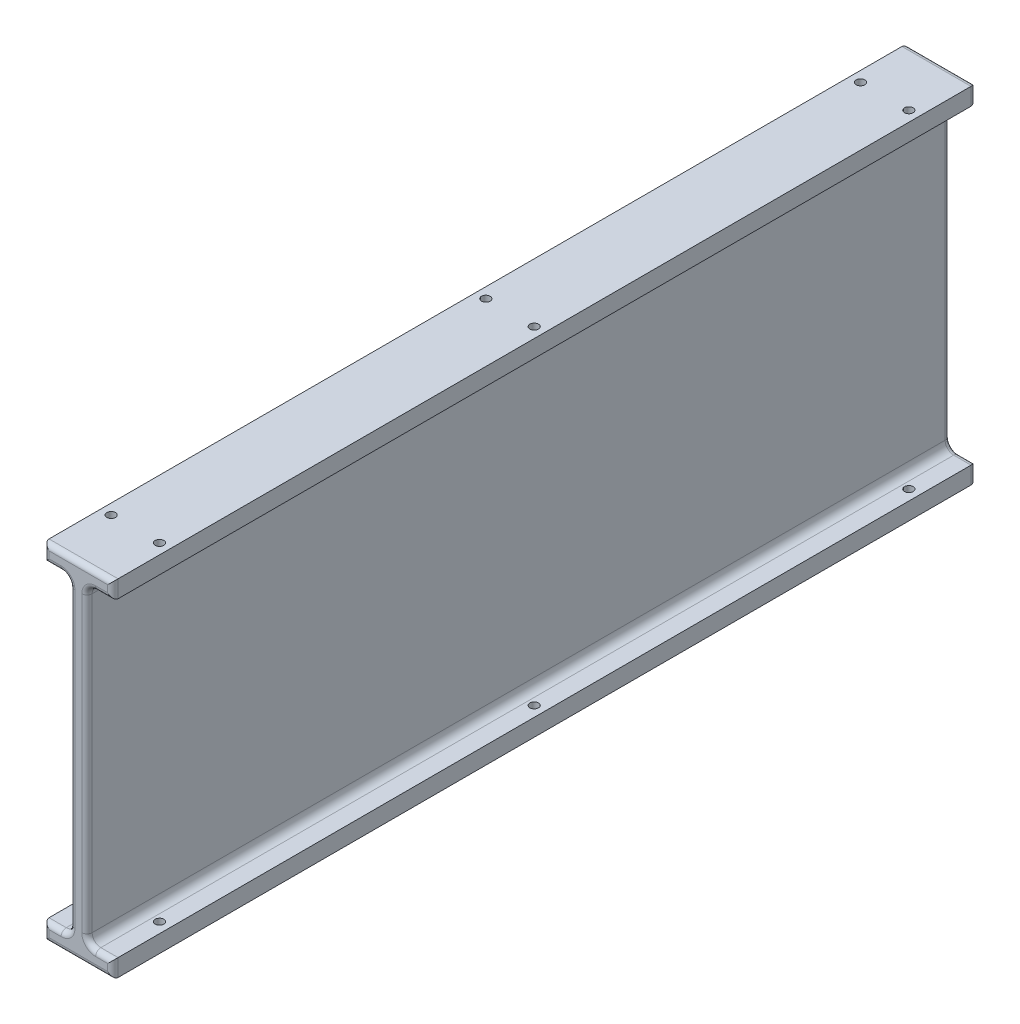
SolidWorks part; units mm, degrees
ref_plane "Front Plane" through (0, 0, 0) normal (0, 0, 1) x (1, 0, 0)
ref_plane "Top Plane" through (0, 0, 0) normal (0, 1, 0) x (1, 0, 0)
ref_plane "Right Plane" through (0, 0, 0) normal (1, 0, 0) x (0, 0, -1)
sketch "Sketch2" plane through (0, 0, 0) normal (0, 0, 1) x (1, 0, 0)
  line L0 (-5, 100) -> (5, 100)
  line L2 (-5, 96.25) -> (-5, 93.75)
  line L3 (-5, -100) -> (5, -100)
  line L4 (5, 85) -> (5, -85)
  line L5 (-4.8101, 96.2025) -> (-4.6914, 93.8272) construction
  line L7 (-20, -90) -> (-10, -90)
  line L8 (-20, -90) -> (-20, -100)
  line L9 (-20, -100) -> (20, -100)
  line L10 (20, -90) -> (20, -100)
  line L17 (4.6914, 93.8272) -> (5, 93.75) construction
  line L18 (-20, 90) -> (-10, 90)
  line L19 (-20, 90) -> (-20, 100)
  line L20 (-20, 100) -> (20, 100)
  line L21 (20, 90) -> (20, 100)
  line L22 (-5, 93.75) -> (-4.6914, 93.8272) construction
  line L23 (-5, 96.25) -> (-4.8101, 96.2025) construction
  line L24 (10, 90) -> (20, 90)
  line L25 (-4.5, 90) -> (4.5, -90) construction
  line L26 (-5, 85) -> (-5, -85)
  line L29 (-4.5, -90) -> (4.5, 90) construction
  line L31 (4.8101, -96.2025) -> (5, -96.25) construction
  line L32 (10, -90) -> (20, -90)
  arc A0 (5, -85) -> (10, -90) centre (10, -85) ccw
  arc A1 (-5, -85) -> (-10, -90) centre (-10, -85) cw
  arc A2 (5, 85) -> (10, 90) centre (10, 85) cw
  arc A3 (-5, 85) -> (-10, 90) centre (-10, 85) ccw
  point P0 (0, 0)
  point P6 (0, -95)
  point P11 (0, -100)
  point P12 (0, 95)
  point P18 (0, 100)
  point P31 (5, -90)
  dimension "D9" = 5
  dimension "D1" = 200
  dimension "D2" = 10
  dimension "D3" = 10
  dimension "D4" = 40
  dimension "D5" = 0
  dimension "D6" = 40
  dimension "D7" = 10
  dimension "D8" = 0
extrude "Boss-Extrude1" add sketch "Sketch2" along normal mid plane 500
fillet "Fillet1" radius 3 32 edges at (-5, 0, -250) (-6.4645, -88.5355, -250) (-15, -90, -250) (-20, -95, -250) (0, -100, -250) (20, -95, -250) (15, -90, -250) (6.4645, -88.5355, -250) (5, 0, -250) (6.4645, 88.5355, -250) (15, 90, -250) (20, 95, -250) (0, 100, -250) (-20, 95, -250) (-15, 90, -250) (-6.4645, 88.5355, -250) (-15, 90, 250) (-20, 95, 250) (0, 100, 250) (20, 95, 250) (15, 90, 250) (6.4645, 88.5355, 250) (5, 0, 250) (6.4645, -88.5355, 250) (15, -90, 250) (20, -95, 250) (0, -100, 250) (-20, -95, 250) (-15, -90, 250) (-6.4645, -88.5355, 250) (-5, 0, 250) (-6.4645, 88.5355, 250)
hole_wizard "Ø5.0mm Dowel Hole1" positions "Sketch6" profile "Sketch7" hole size "Ø5.0" standard "ANSI Metric" end condition through all
sketch "Sketch6" plane through (0, 100, 0) normal (0, 1, 0) x (1, 0, 0)
  line L0 (20, -247) -> (20, 247) construction
  line L1 (-20, -247) -> (-20, 247) construction
  line L2 (20, 247) -> (-20, 247) construction
  line L3 (-20, -247) -> (20, -247) construction
  point P0 (14, 217)
  point P5 (-14, 217)
  point P7 (-14, -217)
  point P9 (14, -217)
  point P18 (-14, 0)
  point P20 (14, 0)
  dimension "D1" = 6
  dimension "D2" = 6
  dimension "D3" = 30
  dimension "D4" = 30
  dimension "D5" = 30
  dimension "D6" = 30
  dimension "D7" = 6
  dimension "D8" = 6
  dimension "D9" = 6
  dimension "D10" = 6
sketch "Sketch7" plane through (14, 100, -217) normal (1, 0, 0) x (0, 0, 1)
  line L0 (0, 0) -> (0, 200)
  line L1 (0, 200) -> (2.5, 200)
  line L2 (2.5, 200) -> (2.5, 0)
  line L5 (2.5, 0) -> (0, 0)
  line L11 (0, -6.35) -> (0, 107.95) construction
  dimension "Thru Hole Dia." = 5
  dimension "Thru Hole Depth" = 200
sketch "Sketch8" plane through (0, 0, 0) normal (0, 1, 0) x (1, 0, 0)
  line L0 (-52.4528, 0) -> (52.4528, 0) construction
  line L1 (0, 49.6738) -> (0, -49.6738) construction
  point P4 (0, 0)
  point P8 (0, 0)
